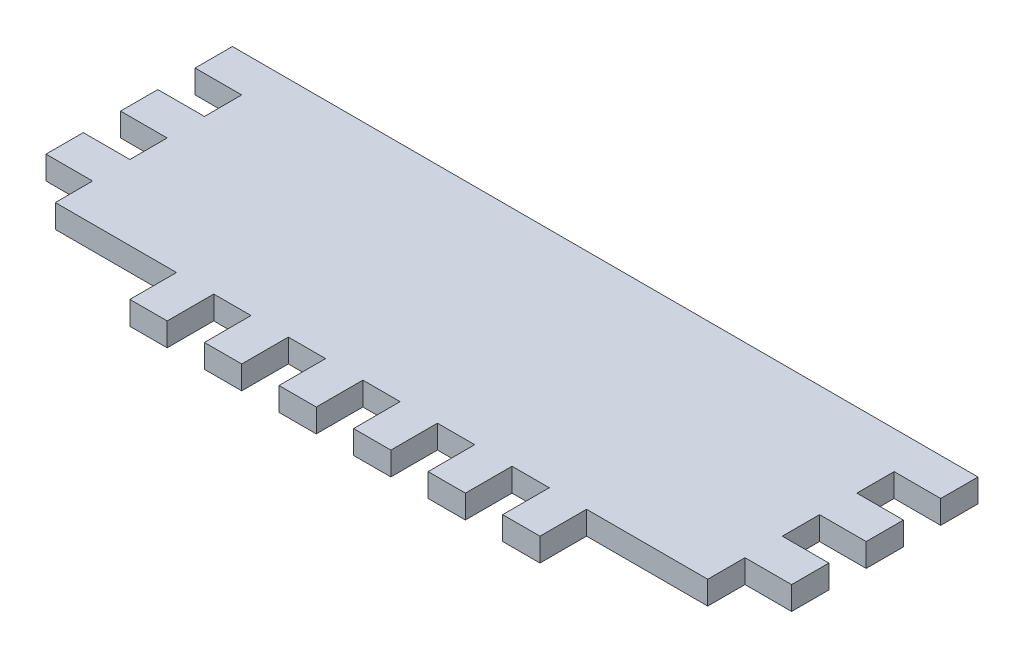
SolidWorks part; units mm, degrees
ref_plane "Front Plane" through (0, 0, 0) normal (0, 0, 1) x (1, 0, 0)
ref_plane "Top Plane" through (0, 0, 0) normal (0, 1, 0) x (1, 0, 0)
ref_plane "Right Plane" through (0, 0, 0) normal (1, 0, 0) x (0, 0, -1)
sketch "Sketch1" plane through (0, 0, 0) normal (0, 1, 0) x (1, 0, 0)
  line L1 (-44.45, -15.24) -> (44.45, -15.24)
  line L2 (-44.45, -15.24) -> (-44.45, 15.24)
  line L3 (-44.45, 15.24) -> (44.45, 15.24)
  line L4 (44.45, -15.24) -> (44.45, 15.24)
  line L5 (-44.45, -15.24) -> (44.45, 15.24) construction
  line L6 (-44.45, 15.24) -> (44.45, -15.24) construction
  point P0 (0, 0)
  dimension "D1" = 88.9
  dimension "D2" = 30.48
extrude "Boss-Extrude1" add sketch "Sketch1" along normal blind 3.175
sketch "Sketch3" plane through (0, 0, 0) normal (0, 1, 0) x (1, 0, 0)
  line L0 (-44.45, -15.24) -> (44.45, -15.24) construction
  line L1 (-27.94, -15.24) -> (-22.86, -15.24)
  line L2 (-27.94, -15.24) -> (-27.94, -18.415)
  line L3 (-27.94, -18.415) -> (-22.86, -18.415)
  line L4 (-22.86, -15.24) -> (-22.86, -18.415)
  line L22 (0, 0) -> (17.78, 0) construction
  line L43 (-17.78, -15.24) -> (-12.7, -15.24)
  line L48 (-17.78, -15.24) -> (-17.78, -18.415)
  line L49 (-17.78, -18.415) -> (-12.7, -18.415)
  line L50 (-12.7, -15.24) -> (-12.7, -18.415)
  line L51 (-7.62, -15.24) -> (-2.54, -15.24)
  line L52 (-7.62, -15.24) -> (-7.62, -18.415)
  line L53 (-7.62, -18.415) -> (-2.54, -18.415)
  line L54 (-2.54, -15.24) -> (-2.54, -18.415)
  line L55 (2.54, -15.24) -> (7.62, -15.24)
  line L56 (2.54, -15.24) -> (2.54, -18.415)
  line L57 (2.54, -18.415) -> (7.62, -18.415)
  line L58 (7.62, -15.24) -> (7.62, -18.415)
  line L59 (12.7, -15.24) -> (17.78, -15.24)
  line L60 (12.7, -15.24) -> (12.7, -18.415)
  line L61 (12.7, -18.415) -> (17.78, -18.415)
  line L62 (17.78, -15.24) -> (17.78, -18.415)
  line L63 (22.86, -15.24) -> (27.94, -15.24)
  line L64 (22.86, -15.24) -> (22.86, -18.415)
  line L65 (22.86, -18.415) -> (27.94, -18.415)
  line L66 (27.94, -15.24) -> (27.94, -18.415)
  dimension "D2" = 5.08
  dimension "D3" = 3.175
extrude "Boss-Extrude2" add sketch "Sketch3" along normal blind 3.175
sketch "Sketch4" plane through (0, 3.175, 0) normal (0, 1, 0) x (1, 0, 0)
  line L0 (2.54, -15.24) -> (2.54, -18.415) construction
  line L1 (-27.94, -18.415) -> (-22.86, -18.415)
  line L2 (-27.94, -18.415) -> (-27.94, -21.59)
  line L3 (-27.94, -21.59) -> (-22.86, -21.59)
  line L4 (-22.86, -18.415) -> (-22.86, -21.59)
  line L5 (-17.78, -18.415) -> (-12.7, -18.415)
  line L6 (-17.78, -18.415) -> (-17.78, -21.59)
  line L7 (-17.78, -21.59) -> (-12.7, -21.59)
  line L8 (-12.7, -18.415) -> (-12.7, -21.59)
  line L9 (-7.62, -18.415) -> (-2.54, -18.415)
  line L10 (-7.62, -18.415) -> (-7.62, -21.59)
  line L11 (-7.62, -21.59) -> (-2.54, -21.59)
  line L12 (-2.54, -18.415) -> (-2.54, -21.59)
  line L13 (2.54, -18.415) -> (7.62, -18.415)
  line L14 (2.54, -18.415) -> (2.54, -21.59)
  line L15 (2.54, -21.59) -> (7.62, -21.59)
  line L16 (7.62, -18.415) -> (7.62, -21.59)
  line L17 (2.54, -18.415) -> (7.62, -18.415) construction
  line L18 (-22.86, -18.415) -> (-22.86, -15.24) construction
  line L19 (12.7, -18.415) -> (17.78, -18.415)
  line L20 (12.7, -18.415) -> (12.7, -21.59)
  line L21 (12.7, -21.59) -> (17.78, -21.59)
  line L22 (17.78, -18.415) -> (17.78, -21.59)
  line L23 (22.86, -18.415) -> (27.94, -18.415)
  line L24 (22.86, -18.415) -> (22.86, -21.59)
  line L25 (22.86, -21.59) -> (27.94, -21.59)
  line L26 (27.94, -18.415) -> (27.94, -21.59)
  line L27 (-22.86, -15.24) -> (-17.78, -15.24) construction
  dimension "D1" = 6.35
extrude "Boss-Extrude3" add sketch "Sketch4" against normal up to surface (3.175 mm away) up to face at (0, 0, 14.4236)
sketch "Sketch5" plane through (0, 3.175, 0) normal (0, 1, 0) x (1, 0, 0)
  line L0 (-44.45, 5.08) -> (-50.8, 5.08)
  line L1 (-44.45, 15.24) -> (-50.8, 15.24)
  line L2 (-44.45, 15.24) -> (-44.45, 10.16)
  line L3 (-44.45, 10.16) -> (-50.8, 10.16)
  line L4 (-50.8, 15.24) -> (-50.8, 10.16)
  line L5 (-44.45, 15.24) -> (-50.8, 10.16) construction
  line L6 (-44.45, 10.16) -> (-50.8, 15.24) construction
  line L7 (-44.45, 5.08) -> (-44.45, 0)
  line L8 (-44.45, 0) -> (-50.8, 0)
  line L9 (-50.8, 5.08) -> (-50.8, 0)
  line L10 (-44.45, 5.08) -> (-50.8, 0) construction
  line L11 (-44.45, 0) -> (-50.8, 5.08) construction
  line L12 (-44.45, -5.08) -> (-50.8, -5.08)
  line L13 (-44.45, -5.08) -> (-44.45, -10.16)
  line L14 (-44.45, -10.16) -> (-50.8, -10.16)
  line L15 (-50.8, -5.08) -> (-50.8, -10.16)
  line L16 (-44.45, -5.08) -> (-50.8, -10.16) construction
  line L17 (-44.45, -10.16) -> (-50.8, -5.08) construction
  line L22 (-44.45, 15.24) -> (-44.45, -15.24) construction
  line L23 (44.45, 15.24) -> (-44.45, 15.24) construction
  line L24 (0, 0) -> (0, 15.24) construction
  line L28 (44.45, -10.16) -> (50.8, -5.08) construction
  line L29 (44.45, -5.08) -> (50.8, -10.16) construction
  line L30 (44.45, 0) -> (50.8, 5.08) construction
  line L31 (44.45, 5.08) -> (50.8, 0) construction
  line L32 (44.45, 10.16) -> (50.8, 15.24) construction
  line L33 (44.45, 15.24) -> (50.8, 10.16) construction
  line L38 (50.8, -5.08) -> (50.8, -10.16)
  line L39 (44.45, -10.16) -> (50.8, -10.16)
  line L40 (44.45, -5.08) -> (44.45, -10.16)
  line L41 (44.45, -5.08) -> (50.8, -5.08)
  line L42 (50.8, 5.08) -> (50.8, 0)
  line L43 (44.45, 0) -> (50.8, 0)
  line L44 (44.45, 5.08) -> (44.45, 0)
  line L45 (50.8, 15.24) -> (50.8, 10.16)
  line L46 (44.45, 10.16) -> (50.8, 10.16)
  line L47 (44.45, 15.24) -> (44.45, 10.16)
  line L48 (44.45, 15.24) -> (50.8, 15.24)
  line L49 (44.45, 5.08) -> (50.8, 5.08)
  line L50 (-44.45, -15.24) -> (-50.8, -15.24) [skipped]
  line L51 (-44.45, -15.24) -> (-44.45, -20.32) [skipped]
  line L52 (-44.45, -20.32) -> (-50.8, -20.32) [skipped]
  line L53 (-50.8, -15.24) -> (-50.8, -20.32) [skipped]
  line L54 (-44.45, -15.24) -> (-50.8, -20.32) construction
  line L55 (-44.45, -20.32) -> (-50.8, -15.24) construction
  point P4 (-47.625, 12.7)
  point P12 (-47.625, 2.54)
  point P17 (-47.625, -7.62)
  point P18 (-47.625, -17.78)
  point P43 (47.625, -7.62)
  point P44 (47.625, 2.54)
  point P45 (47.625, 12.7)
  dimension "D1" = 6.35
  dimension "D2" = 5.08
  dimension "D4" = 10.16
  dimension "D3" = 4
extrude "Boss-Extrude4" add sketch "Sketch5" against normal up to surface (3.175 mm away) up to face at (0, 0, 15.7843)
